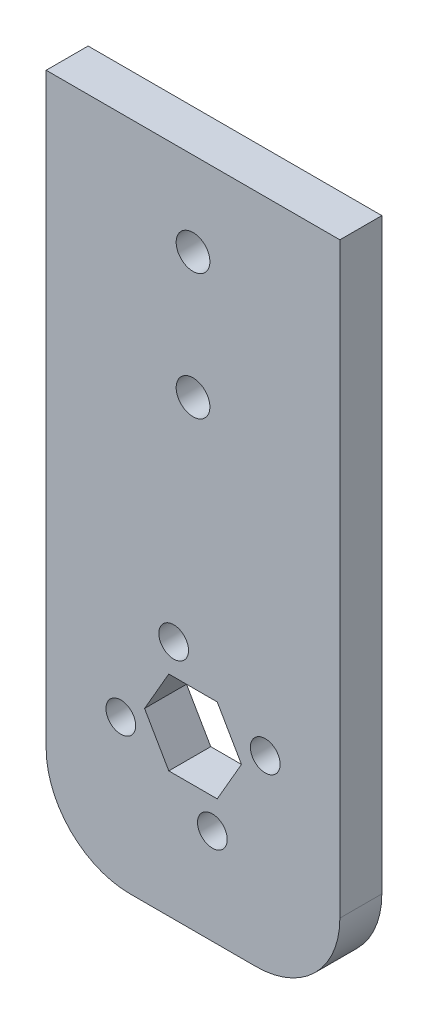
SolidWorks part; units mm, degrees
material "6061 Alloy"
ref_plane "Front Plane" through (0, 0, 0) normal (0, 0, 1) x (1, 0, 0)
ref_plane "Top Plane" through (0, 0, 0) normal (0, 1, 0) x (1, 0, 0)
ref_plane "Right Plane" through (0, 0, 0) normal (1, 0, 0) x (0, 0, -1)
sketch "Sketch1" plane through (0, 0, 0) normal (0, 0, 1) x (1, 0, 0)
  line L1 (0, 0) -> (-44.45, 0)
  line L2 (0, 0) -> (0, 101.6)
  line L3 (0, 101.6) -> (-44.45, 101.6)
  line L4 (-44.45, 0) -> (-44.45, 101.6)
  dimension "D1" = 101.6
  dimension "D2" = 44.45
extrude "Boss-Extrude2" add sketch "Sketch1" along normal blind 6.35
sketch "Sketch3" plane through (0, 0, 0) normal (0, 0, -1) x (-1, 0, 0)
  line L0 (22.225, 101.6) -> (22.225, 0) construction
  line L1 (0, 101.6) -> (44.45, 101.6) construction
  line L2 (44.45, 0) -> (0, 0) construction
  point P3 (22.225, 50.8)
fillet "Fillet1" radius 12.7 2 edges at (-44.45, 0, 3.175) (0, 0, 3.175)
hole_wizard "#7 (0.201) Diameter Hole2" positions "Sketch11" profile "Sketch12" hole size "#7" standard "ANSI Inch" end condition through all
sketch "Sketch11" plane through (0, 0, 0) normal (0, 0, -1) x (-1, 0, 0)
  line L0 (22.225, 101.6) -> (22.225, 0) construction
  line L1 (0, 101.6) -> (44.45, 101.6) construction
  point P0 (22.225, 88.9)
  point P4 (22.225, 69.85)
  dimension "D1" = 19.05
  dimension "D2" = 12.7
sketch "Sketch12" plane through (-22.225, 88.9, 0) normal (1, 0, 0) x (0, 1, 0)
  line L0 (0, 0) -> (0, 6.35)
  line L1 (0, 6.35) -> (2.5527, 6.35)
  line L2 (2.5527, 6.35) -> (2.5527, 0)
  line L5 (2.5527, 0) -> (0, 0)
  line L11 (0, -6.35) -> (0, 107.95) construction
  dimension "Thru Hole Dia." = 5.1054
  dimension "Thru Hole Depth" = 6.35
sketch "Sketch14" plane through (0, 0, 6.35) normal (0, 0, 1) x (1, 0, 0)
  line L0 (-22.225, 101.6) -> (-22.225, 0) construction
  line L1 (-14.8927, 25.4) -> (-18.5588, 31.75)
  line L2 (-18.5588, 31.75) -> (-25.8912, 31.75)
  line L3 (-25.8912, 31.75) -> (-29.5573, 25.4)
  line L4 (-29.5573, 25.4) -> (-25.8912, 19.05)
  line L5 (-25.8912, 19.05) -> (-18.5588, 19.05)
  line L6 (-18.5588, 19.05) -> (-14.8927, 25.4)
  line L7 (-31.75, 0) -> (-12.7, 0) construction
  circle A0 centre (-22.225, 25.4) radius 6.35 construction
  point P12 (-22.225, 31.75)
  dimension "D1" = 12.7
  dimension "D2" = 25.4
extrude "Cut-Extrude1" cut sketch "Sketch14" against normal through all
sketch "Sketch22" plane through (0, 0, 6.35) normal (0, 0, 1) x (1, 0, 0)
  circle A0 centre (-25.1532, 36.3282) radius 2.05
  circle A1 centre (-11.2968, 28.3282) radius 2.05
  circle A2 centre (-19.2968, 14.4718) radius 2.05
  circle A3 centre (-33.1532, 22.4718) radius 2.05
hole_wizard "M4 Clearance Hole1" positions "Sketch25" profile "Sketch24" hole size "M4" standard "ANSI Metric" end condition through all
sketch "Sketch25" plane through (0, 0, 0) normal (0, 0, -1) x (-1, 0, 0)
  point P0 (11.2968, 28.3282)
  point P3 (25.1532, 36.3282)
  point P6 (33.1532, 22.4718)
  point P9 (19.2968, 14.4718)
sketch "Sketch24" plane through (-11.2968, 28.3282, 0) normal (1, 0, 0) x (0, 1, 0)
  line L0 (0, 0) -> (0, 6.35)
  line L1 (0, 6.35) -> (2.25, 6.35)
  line L2 (2.25, 6.35) -> (2.25, 0)
  line L5 (2.25, 0) -> (0, 0)
  line L11 (0, -6.35) -> (0, 107.95) construction
  dimension "Thru Hole Dia." = 4.5
  dimension "Thru Hole Depth" = 6.35
sketch "Sketch26" plane through (0, 0, 0) normal (0, 0, -1) x (-1, 0, 0)
  line L0 (14.8927, 25.4) -> (29.5573, 25.4) construction
  line L1 (18.5588, 19.05) -> (25.8912, 31.75) construction
  circle A0 centre (22.225, 25.4) radius 7.3323
  point P11 (22.225, 25.4)
